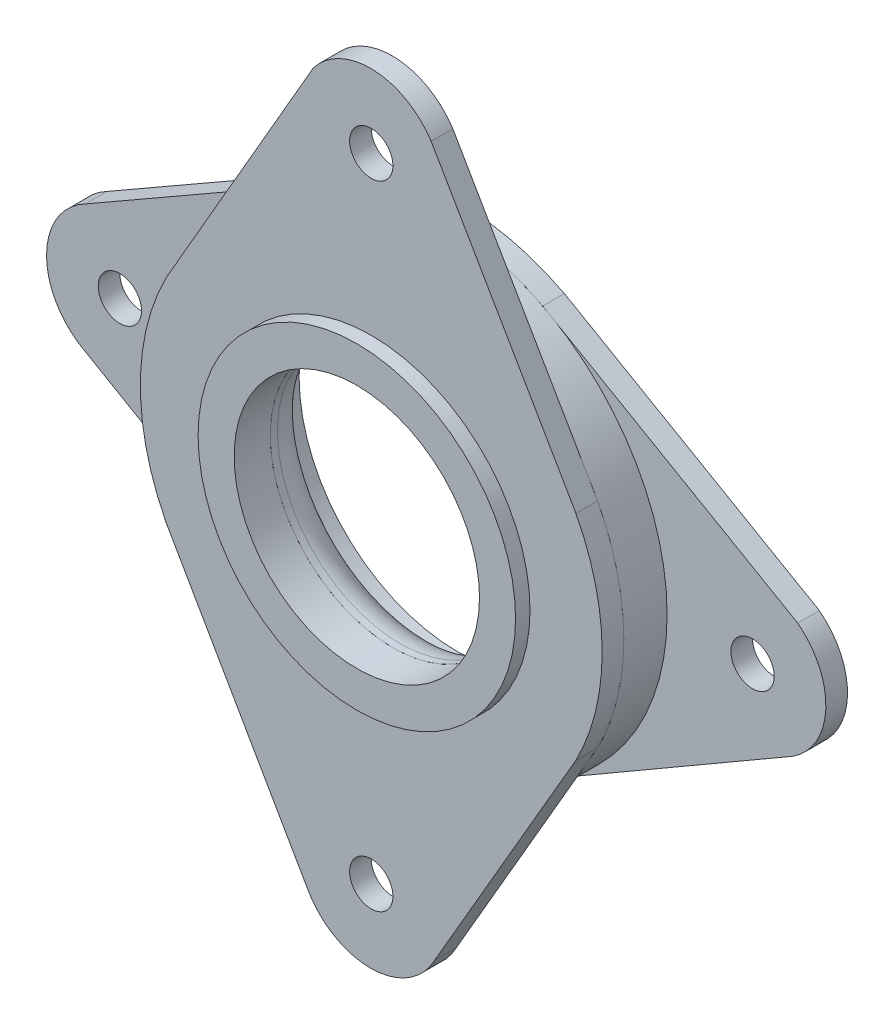
SolidWorks part; units mm, degrees
material "ABS"
ref_plane "Front Plane" through (0, 0, 0) normal (0, 0, 1) x (1, 0, 0)
ref_plane "Top Plane" through (0, 0, 0) normal (0, 1, 0) x (1, 0, 0)
ref_plane "Right Plane" through (0, 0, 0) normal (1, 0, 0) x (0, 0, -1)
sketch "Sketch1" plane through (0, 0, 0) normal (0, 0, 1) x (1, 0, 0)
  line L1 (7.3794, 14.1966) -> (25.0466, 4.0094)
  line L2 (-24.3098, 4.4793) -> (-7.325, 14.2248)
  line L3 (-24.3029, -4.3932) -> (-7.4267, -14.1719)
  line L4 (7.408, -14.1817) -> (24.7169, -4.1525)
  line L7 (20.4006, 0) -> (41.1933, 0) construction
  arc A0 (-7.4267, -14.1719) -> (7.408, -14.1817) centre (0, 0) ccw construction
  circle A1 centre (0, 0) radius 27 construction
  arc A4 (24.7169, -4.1525) -> (25.0466, 4.0094) centre (22, 0.0449) ccw
  arc A5 (-7.4267, -14.1719) -> (7.408, -14.1817) centre (0, 0) ccw
  arc A6 (-24.3098, 4.4793) -> (-24.3029, -4.3932) centre (-22, 0.0449) ccw
  arc A7 (7.3794, 14.1966) -> (-7.325, 14.2248) centre (0, 0) ccw construction
  arc A8 (7.3794, 14.1966) -> (-7.325, 14.2248) centre (0, 0) ccw
  point P7 (0, 0)
  dimension "D1" = 32
  dimension "D2" = 54
  dimension "D7" = 10
  dimension "D6" = 22
extrude "Boss-Extrude1" add sketch "Sketch1" along normal blind 1.5
sketch "Sketch2" plane through (0, 0, 1.5) normal (0, 0, 1) x (1, 0, 0)
  line L0 (31.1876, 0) -> (-31.1876, 0) construction
  circle A0 centre (-21.92, 0) radius 1.5
  circle A1 centre (21.92, 0) radius 1.5
  circle A2 centre (0, 0) radius 8.5
  point P9 (0, 0)
  dimension "D1" = 17
  dimension "D2" = 3
  dimension "D3" = 3
  dimension "D4" = 21.92
  dimension "D5" = 21.92
extrude "Cut-Extrude1" cut sketch "Sketch2" against normal through all
ref_plane "Plane1" through (0, 0, 3) normal (0, 0, 1) x (1, 0, 0)
mirror "Mirror2" about plane through (0, 0, 3) normal (0, 0, 1) of bodies 102
move or copy body "Body-Move/Copy1" bodies to move or copy 104 copy no rotation origin (0, 0, 0) rotation axis (0, 0, 1) rotation angle 90
sketch "Sketch3" plane through (0, 0, 3) normal (0, 0, 1) x (1, 0, 0)
  circle A0 centre (0, 0) radius 16
  circle A1 centre (0, 0) radius 8.5
  dimension "D1" = 32
extrude "Boss-Extrude2" add sketch "Sketch3" along normal blind 1.5 and the other way blind 1.5 separate body
sketch "Sketch4" plane through (0, 0, 0) normal (0, 0, -1) x (-1, 0, 0)
  circle A0 centre (0, 0) radius 11
  dimension "D1" = 22
extrude "Cut-Extrude2" cut sketch "Sketch4" against normal up to surface (1.5 mm away) up to face at (-20.42, 0, 1.5)
fillet "Fillet1" radius 2.5 1 edges at (8.5, 0, 1.5)
sketch "Sketch6" plane through (0, 0, 6) normal (0, 0, 1) x (1, 0, 0)
  circle A0 centre (0, 0) radius 8.5
  circle A1 centre (0, 0) radius 11
  dimension "D1" = 22
  dimension "D2" = 17
extrude "Boss-Extrude4" add sketch "Sketch6" along normal blind 1
